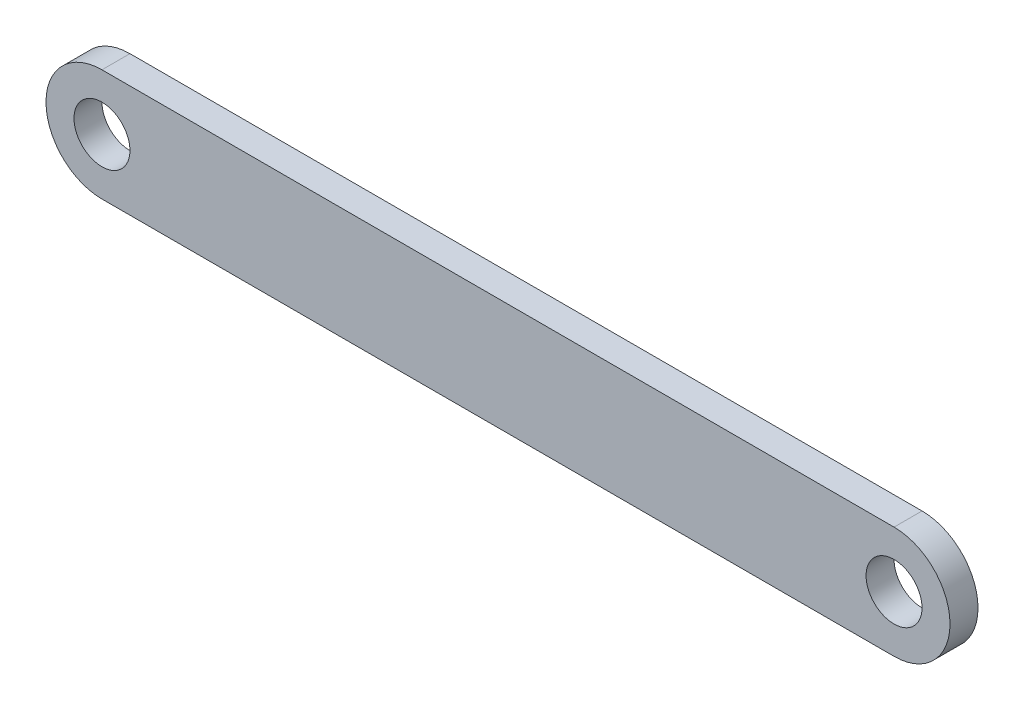
SolidWorks part; units mm, degrees
ref_plane "Спереди" through (0, 0, 0) normal (0, 0, 1) x (1, 0, 0)
ref_plane "Сверху" through (0, 0, 0) normal (0, 1, 0) x (1, 0, 0)
ref_plane "Справа" through (0, 0, 0) normal (1, 0, 0) x (0, 0, -1)
sketch "Sketch1" plane through (0, 0, 0) normal (0, 0, 1) x (1, 0, 0)
  line L0 (0, 0) -> (-28.3062, 0)
  line L1 (-28.3062, 2) -> (0, 2)
  line L2 (-28.3062, -2) -> (0, -2)
  circle A0 centre (0, 0) radius 1
  circle A1 centre (0, 0) radius 2
  circle A2 centre (-28.3062, 0) radius 1
  circle A3 centre (-28.3062, 0) radius 2
extrude "Extrude1" add sketch "Sketch1" along normal blind 1
